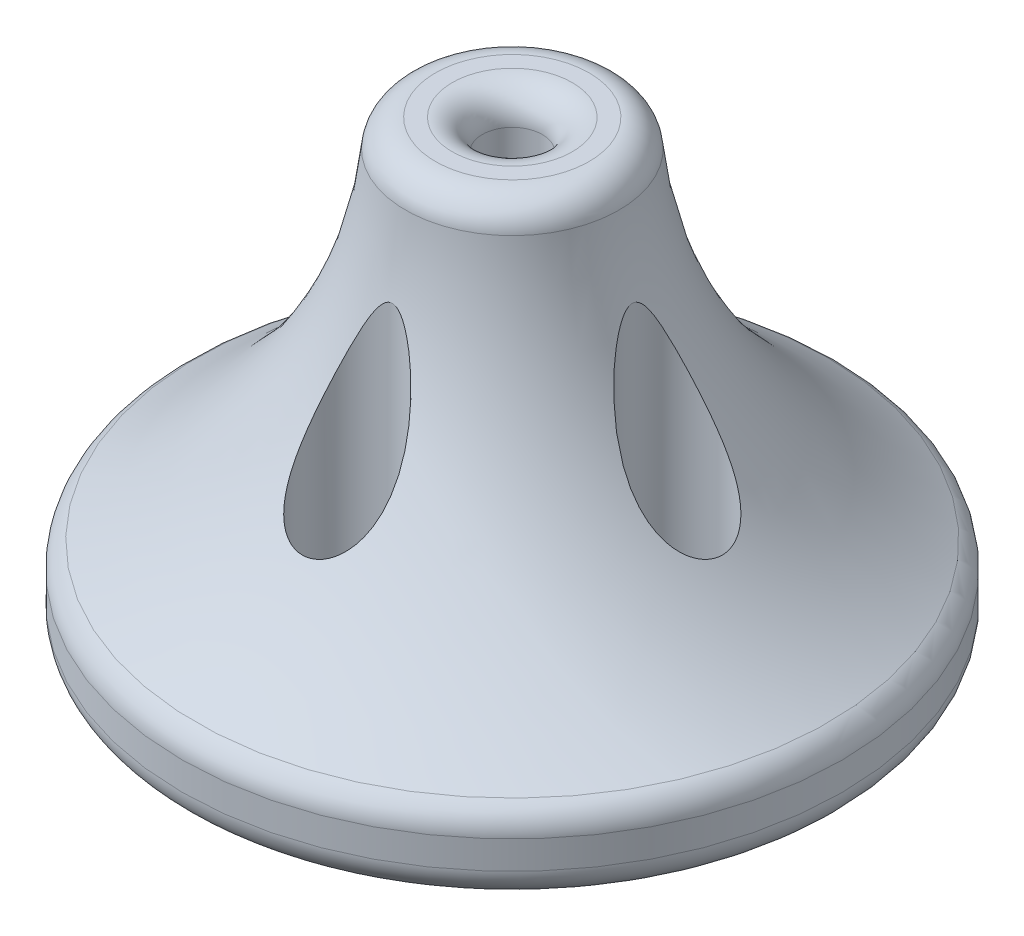
SolidWorks part; units mm, degrees
material "ABS"
ref_plane "Alzado" through (0, 0, 0) normal (0, 0, 1) x (1, 0, 0)
ref_plane "Planta" through (0, 0, 0) normal (0, 1, 0) x (1, 0, 0)
ref_plane "Vista lateral" through (0, 0, 0) normal (1, 0, 0) x (0, 0, -1)
sketch "Croquis1" plane through (0, 0, 0) normal (0, 0, 1) x (1, 0, 0)
  line L0 (0, 0) -> (0, 127.6397) construction
  line L1 (-4, 0) -> (-20, 0)
  line L2 (-2, 28) -> (-2, 2)
  line L3 (-4, 30) -> (-5.1237, 30)
  line L4 (-22, 2) -> (-22, 3.8691)
  arc A1 (-7.1149, 28.1869) -> (-21.0615, 5.5641) centre (-36.9837, 30.9902) cw
  arc A2 (-2, 2) -> (-4, 0) centre (-4, 2) cw
  arc A3 (-2, 28) -> (-4, 30) centre (-4, 28) ccw
  arc A4 (-7.1149, 28.1869) -> (-5.1237, 30) centre (-5.1237, 28) cw
  arc A5 (-22, 3.8691) -> (-21.0615, 5.5641) centre (-20, 3.8691) cw
  arc A6 (-20, 0) -> (-22, 2) centre (-20, 2) cw
  point P12 (-2, 0)
  point P15 (-2, 30)
  point P18 (-7, 30)
  point P21 (-22, 5)
  point P24 (-22, 0)
  dimension "D3" = 20
  dimension "D5" = 5
  dimension "D6" = 30
  dimension "D7" = 2
  dimension "D1" = 4
  dimension "D2" = 30
  dimension "D4" = 5
revolve "Revolución1" add sketch "Croquis1" angle 360 about L0
sketch "Croquis2" plane through (0, 0, 0) normal (0, -1, 0) x (1, 0, 0)
  line L0 (0, 20) -> (0, -20) construction
  line L1 (-20, 0) -> (20, 0) construction
  circle A0 centre (0, 0) radius 20 construction
  circle A1 centre (0, 0) radius 20 construction
  circle A2 centre (-11, 0) radius 3
  circle A3 centre (11, 0) radius 3
  circle A4 centre (0, 11) radius 3
  circle A5 centre (0, -11) radius 3
  dimension "D1" = 6
  dimension "D2" = 9
  dimension "D3" = 9
extrude "Cortar-Extruir1" cut sketch "Croquis2" against normal blind 60 contours A2 | A5 | A3 | A4
